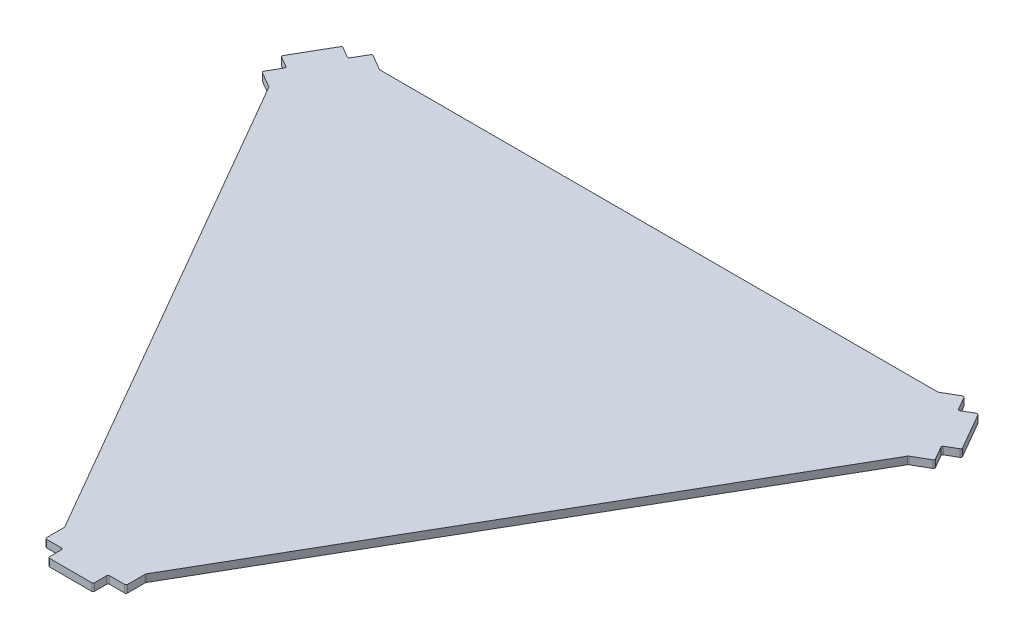
SolidWorks part; units mm, degrees
ref_plane "前基準面" through (0, 0, 0) normal (0, 0, 1) x (1, 0, 0)
ref_plane "上基準面" through (0, 0, 0) normal (0, 1, 0) x (1, 0, 0)
ref_plane "右基準面" through (0, 0, 0) normal (1, 0, 0) x (0, 0, -1)
sketch "草圖1" plane through (0, 0, 0) normal (0, 1, 0) x (1, 0, 0)
  line L0 (27.134, -175.8349) -> (47, -141.426)
  line L1 (-146.0422, 192.933) -> (146.0422, 192.933)
  line L2 (193.0422, 111.5266) -> (47, -141.426)
  line L3 (-193.0422, 111.5266) -> (-47, -141.426)
  line L6 (-47, -141.426) -> (-27.134, -175.8349)
  line L7 (-27, -176.3349) -> (-27, -188.067)
  line L8 (-26, -189.067) -> (-16, -189.067)
  line L9 (-15, -190.067) -> (-15, -198.067)
  line L10 (-14, -199.067) -> (14, -199.067)
  line L11 (15, -198.067) -> (15, -190.067)
  line L12 (16, -189.067) -> (26, -189.067)
  line L13 (27, -188.067) -> (27, -176.3349)
  line L14 (-212.9083, 145.9356) -> (-193.0422, 111.5266)
  line L20 (-146.0422, 192.933) -> (-185.7743, 192.933)
  line L21 (-186.2743, 193.067) -> (-196.4346, 198.933)
  line L22 (-197.8006, 198.567) -> (-202.8006, 189.9067)
  line L23 (-204.1666, 189.5407) -> (-211.0948, 193.5407)
  line L24 (-212.4608, 193.1747) -> (-226.4608, 168.926)
  line L25 (-226.0948, 167.5599) -> (-219.1666, 163.5599)
  line L26 (-218.8006, 162.1939) -> (-223.8006, 153.5337)
  line L27 (-223.4346, 152.1676) -> (-213.2743, 146.3016)
  line L28 (185.7743, 192.933) -> (146.0422, 192.933)
  line L34 (193.0422, 111.5266) -> (212.9083, 145.9356)
  line L35 (213.2743, 146.3016) -> (223.4346, 152.1676)
  line L36 (223.8006, 153.5337) -> (218.8006, 162.1939)
  line L37 (219.1666, 163.5599) -> (226.0948, 167.5599)
  line L38 (226.4608, 168.926) -> (212.4608, 193.1747)
  line L39 (211.0948, 193.5407) -> (204.1666, 189.5407)
  line L40 (202.8006, 189.9067) -> (197.8006, 198.567)
  line L41 (196.4346, 198.933) -> (186.2743, 193.067)
  arc A6 (-27, -176.3349) -> (-27.134, -175.8349) centre (-28, -176.3349) ccw
  arc A7 (-27, -188.067) -> (-26, -189.067) centre (-26, -188.067) ccw
  arc A8 (-15, -190.067) -> (-16, -189.067) centre (-16, -190.067) ccw
  arc A9 (-15, -198.067) -> (-14, -199.067) centre (-14, -198.067) ccw
  arc A10 (14, -199.067) -> (15, -198.067) centre (14, -198.067) ccw
  arc A11 (16, -189.067) -> (15, -190.067) centre (16, -190.067) ccw
  arc A12 (26, -189.067) -> (27, -188.067) centre (26, -188.067) ccw
  arc A13 (27.134, -175.8349) -> (27, -176.3349) centre (28, -176.3349) ccw
  arc A20 (-186.2743, 193.067) -> (-185.7743, 192.933) centre (-185.7743, 193.933) ccw
  arc A21 (-196.4346, 198.933) -> (-197.8006, 198.567) centre (-196.9346, 198.067) ccw
  arc A22 (-204.1666, 189.5407) -> (-202.8006, 189.9067) centre (-203.6666, 190.4067) ccw
  arc A23 (-211.0948, 193.5407) -> (-212.4608, 193.1747) centre (-211.5948, 192.6747) ccw
  arc A24 (-226.4608, 168.926) -> (-226.0948, 167.5599) centre (-225.5948, 168.426) ccw
  arc A25 (-218.8006, 162.1939) -> (-219.1666, 163.5599) centre (-219.6666, 162.6939) ccw
  arc A26 (-223.8006, 153.5337) -> (-223.4346, 152.1676) centre (-222.9346, 153.0337) ccw
  arc A27 (-212.9083, 145.9356) -> (-213.2743, 146.3016) centre (-213.7743, 145.4356) ccw
  arc A34 (213.2743, 146.3016) -> (212.9083, 145.9356) centre (213.7743, 145.4356) ccw
  arc A35 (223.4346, 152.1676) -> (223.8006, 153.5337) centre (222.9346, 153.0337) ccw
  arc A36 (219.1666, 163.5599) -> (218.8006, 162.1939) centre (219.6666, 162.6939) ccw
  arc A37 (226.0948, 167.5599) -> (226.4608, 168.926) centre (225.5948, 168.426) ccw
  arc A38 (212.4608, 193.1747) -> (211.0948, 193.5407) centre (211.5948, 192.6747) ccw
  arc A39 (202.8006, 189.9067) -> (204.1666, 189.5407) centre (203.6666, 190.4067) ccw
  arc A40 (197.8006, 198.567) -> (196.4346, 198.933) centre (196.9346, 198.067) ccw
  arc A41 (185.7743, 192.933) -> (186.2743, 193.067) centre (185.7743, 193.933) ccw
extrude "填料-伸長1" add sketch "草圖1" along normal blind 5
